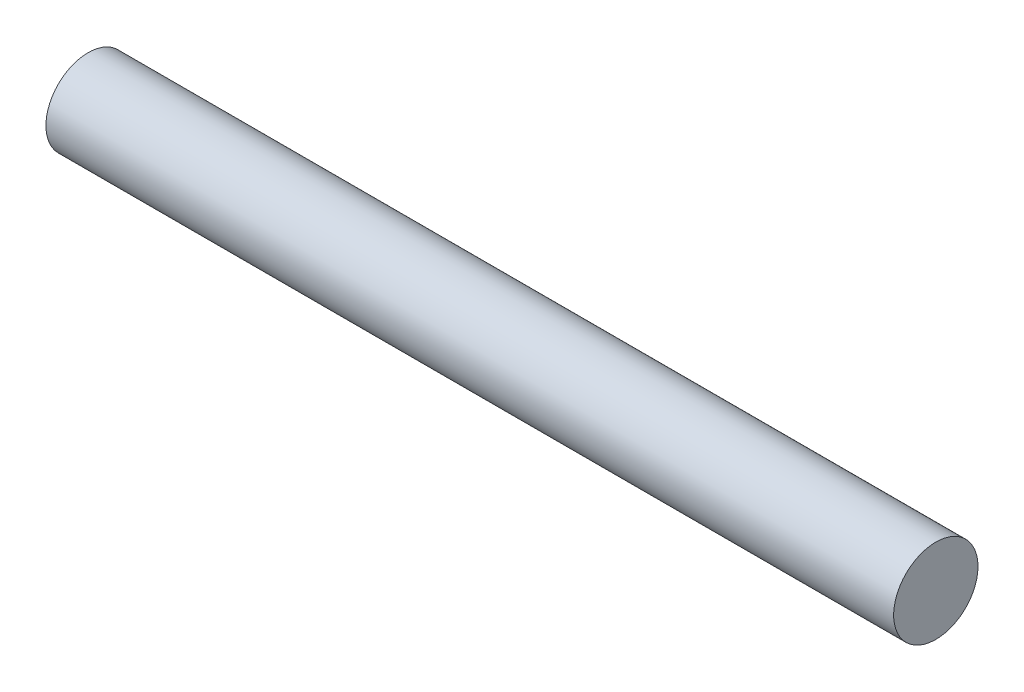
SolidWorks part; units mm, degrees
material "6061 Alloy"
ref_plane "Front Plane" through (0, 0, 0) normal (0, 0, 1) x (1, 0, 0)
ref_plane "Top Plane" through (0, 0, 0) normal (0, 1, 0) x (1, 0, 0)
ref_plane "Right Plane" through (0, 0, 0) normal (1, 0, 0) x (0, 0, -1)
sketch "Sketch1" plane through (0, 0, 0) normal (1, 0, 0) x (0, 0, -1)
  circle A0 centre (0, 0) radius 3
  dimension "D1" = 6
extrude "Boss-Extrude1" add sketch "Sketch1" along normal blind 60.3
